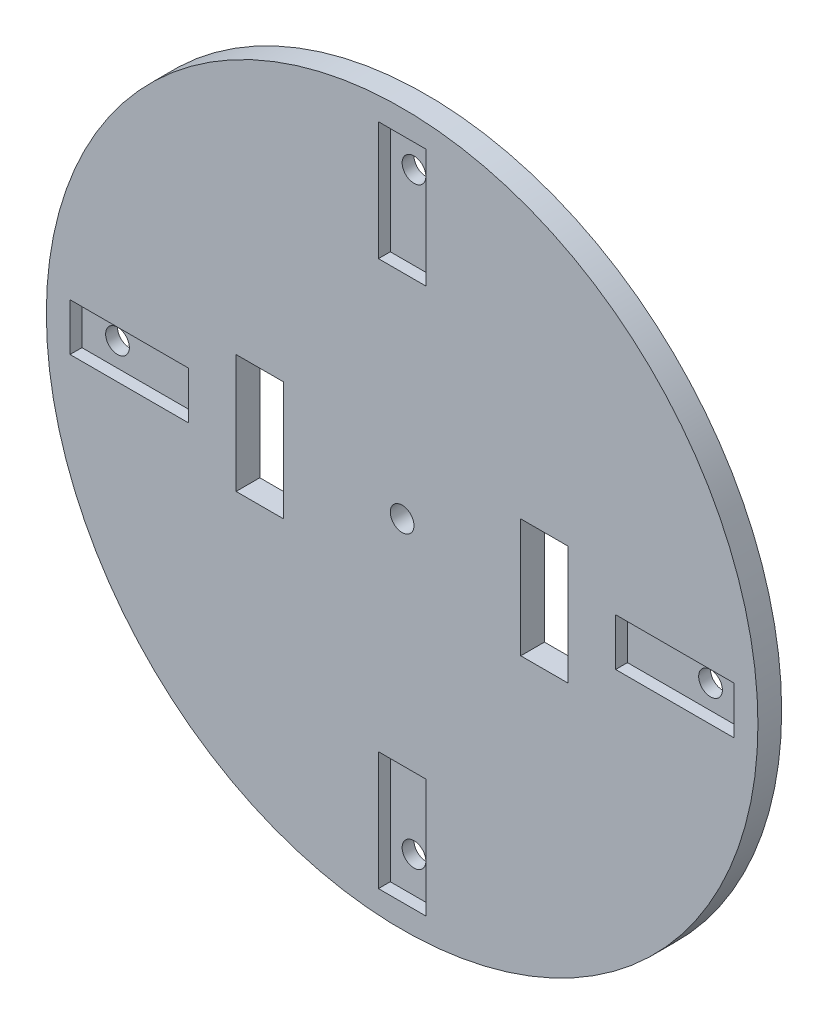
SolidWorks part; units mm, degrees
ref_plane "前视基准面" through (0, 0, 0) normal (0, 0, 1) x (1, 0, 0)
ref_plane "上视基准面" through (0, 0, 0) normal (0, 1, 0) x (1, 0, 0)
ref_plane "右视基准面" through (0, 0, 0) normal (1, 0, 0) x (0, 0, -1)
sketch "草图1" plane through (0, 0, 0) normal (0, 0, 1) x (1, 0, 0)
  circle A0 centre (-15.3908, 6.9303) radius 150
  circle A1 centre (-15.3908, 6.9303) radius 5
extrude "凸台-拉伸1" add sketch "草图1" along normal blind 10
sketch "草图2" plane through (0, 0, 10) normal (0, 0, 1) x (1, 0, 0)
  line L0 (124.6092, 16.9303) -> (74.6092, 16.9303)
  line L1 (124.6092, 16.9303) -> (124.6092, -3.0697)
  line L2 (-25.3908, 146.9303) -> (-5.3908, 146.9303)
  line L3 (-25.3908, 146.9303) -> (-25.3908, 96.9303)
  line L4 (-25.3908, 96.9303) -> (-5.3908, 96.9303)
  line L5 (-5.3908, 146.9303) -> (-5.3908, 96.9303)
  line L6 (-15.3908, 96.9303) -> (-15.3908, 146.9303) construction
  line L7 (-25.3908, 121.9303) -> (-5.3908, 121.9303) construction
  line L8 (124.6092, -3.0697) -> (74.6092, -3.0697)
  line L9 (74.6092, 16.9303) -> (74.6092, -3.0697)
  line L10 (-5.3908, -133.0697) -> (-5.3908, -83.0697)
  line L11 (-5.3908, -133.0697) -> (-25.3908, -133.0697)
  line L12 (-25.3908, -133.0697) -> (-25.3908, -83.0697)
  line L13 (-5.3908, -83.0697) -> (-25.3908, -83.0697)
  line L14 (-155.3908, -3.0697) -> (-105.3908, -3.0697)
  line L15 (-155.3908, -3.0697) -> (-155.3908, 16.9303)
  line L16 (-155.3908, 16.9303) -> (-105.3908, 16.9303)
  line L17 (-105.3908, -3.0697) -> (-105.3908, 16.9303)
  circle A0 centre (-15.3908, 6.9303) radius 5 construction
  point P20 (-15.3908, 6.9303)
  dimension "D1" = 20
  dimension "D2" = 50
  dimension "D3" = 90
  dimension "D4" = 4
extrude "切除-拉伸1" cut sketch "草图2" against normal blind 5
sketch "草图3" plane through (0, 0, 10) normal (0, 0, 1) x (1, 0, 0)
  line L0 (54.6092, -18.0697) -> (54.6092, 31.9303)
  line L5 (54.6092, -18.0697) -> (34.6092, -18.0697)
  line L6 (34.6092, -18.0697) -> (34.6092, 31.9303)
  line L7 (-85.3908, 31.9303) -> (-65.3908, 31.9303)
  line L8 (-85.3908, 31.9303) -> (-85.3908, -18.0697)
  line L9 (-85.3908, -18.0697) -> (-65.3908, -18.0697)
  line L10 (-65.3908, 31.9303) -> (-65.3908, -18.0697)
  line L11 (-75.3908, -18.0697) -> (-75.3908, 31.9303) construction
  line L12 (-85.3908, 6.9303) -> (-65.3908, 6.9303) construction
  line L13 (54.6092, 31.9303) -> (34.6092, 31.9303)
  line L14 (-105.3908, -3.0697) -> (-105.3908, 16.9303) construction
  point P0 (-15.3908, 6.9303)
  point P10 (-15.3908, 6.9303)
  dimension "D1" = 2
  dimension "D2" = 20
  dimension "D3" = 50
  dimension "D4" = 140
  dimension "D5" = 70
  dimension "D6" = 20
sketch "草图4" plane through (0, 0, 5) normal (0, 0, 1) x (1, 0, 0)
  line L0 (74.6092, -3.0697) -> (124.6092, -3.0697) construction
  line L1 (124.6092, -3.0697) -> (124.6092, 16.9303) construction
  circle A0 centre (109.6092, 6.9303) radius 5
  circle A1 centre (-15.3908, -118.0697) radius 5
  circle A2 centre (-140.3908, 6.9303) radius 5
  circle A3 centre (-15.3908, 131.9303) radius 5
  point P15 (-15.3908, 6.9303)
  dimension "D1" = 10
  dimension "D2" = 15
  dimension "D3" = 4
extrude "切除-拉伸3" cut sketch "草图4" against normal through all
extrude "切除-拉伸4" cut sketch "草图3" against normal through all both and the other way through all
